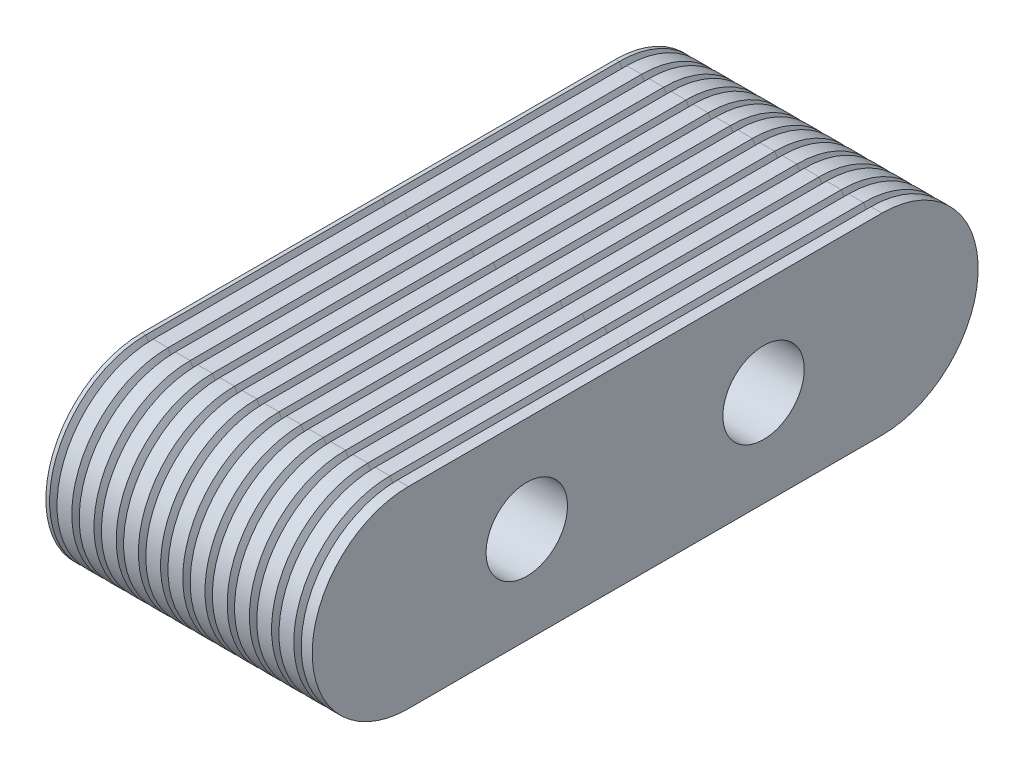
SolidWorks part; units mm, degrees
ref_plane "Front Plane" through (0, 0, 0) normal (0, 0, 1) x (1, 0, 0)
ref_plane "Top Plane" through (0, 0, 0) normal (0, 1, 0) x (1, 0, 0)
ref_plane "Right Plane" through (0, 0, 0) normal (1, 0, 0) x (0, 0, -1)
sketch "Sketch2" plane through (0, 0, 0) normal (1, 0, 0) x (0, 0, -1)
  line L0 (16, 0) -> (-16, 0) construction
  line L1 (16, -8) -> (-16, -8) construction
  line L2 (16, 8) -> (-16, 8) construction
  line L3 (16, -6.5) -> (-16, -6.5)
  line L4 (16, 6.5) -> (-16, 6.5)
  arc A0 (16, -8) -> (16, 8) centre (16, 0) ccw construction
  arc A1 (-16, 8) -> (-16, -8) centre (-16, 0) ccw construction
  arc A2 (-16, 6.5) -> (-16, -6.5) centre (-16, 0) ccw
  arc A3 (16, -6.5) -> (16, 6.5) centre (16, 0) ccw
  point P2 (0, 0)
  dimension "D1" = 32
  dimension "D2" = 16
  dimension "D3" = 1.5
extrude "Boss-Extrude1" add sketch "Sketch2" along normal mid plane 18
sketch "Sketch3" plane through (0, 0, 0) normal (0, 0, 1) x (1, 0, 0)
  line L0 (-8.7475, 6.5) -> (-8.4975, 6.067)
  line L1 (-8.4975, 6.067) -> (-8.2475, 6.5)
  line L2 (-8.2475, 6.5) -> (-8.7475, 6.5)
  line L4 (9, 6.5) -> (-9, 6.5) construction
  point P2 (-8.7475, 6.5)
  dimension "D1" = 0.5
  dimension "D2" = 0.2525
sketch "Sketch4" plane through (-9, 0, 0) normal (-1, 0, 0) x (0, 0, 1)
  line L6 (-16, -6.5) -> (16, -6.5)
  line L7 (16, 6.5) -> (-16, 6.5)
  line L8 (-16, -6.5) -> (16, -6.5)
  line L9 (16, 6.5) -> (-16, 6.5)
  arc A6 (-16, 6.5) -> (-16, -6.5) centre (-16, 0) ccw
  arc A7 (16, -6.5) -> (16, 6.5) centre (16, 0) ccw
  arc A8 (-16, 6.5) -> (-16, -6.5) centre (-16, 0) ccw
  arc A9 (16, -6.5) -> (16, 6.5) centre (16, 0) ccw
  dimension "D1" = 0
sweep "Cut-Sweep1" cut profiles "Sketch3" path "Sketch4"
pattern_linear "LPattern1" count 12 spacing 1.5 along (1, 0, 0) of "Cut-Sweep1"
sketch "Sketch5" plane through (9, 0, 0) normal (1, 0, 0) x (0, 0, -1)
  line L0 (-8, 0) -> (8, 0) construction
  circle A0 centre (-8, 0) radius 2.75
  circle A1 centre (8, 0) radius 2.75
  point P4 (0, 0)
  dimension "D1" = 5.5
  dimension "D2" = 16
extrude "Cut-Extrude1" cut sketch "Sketch5" against normal through all both and the other way through all
